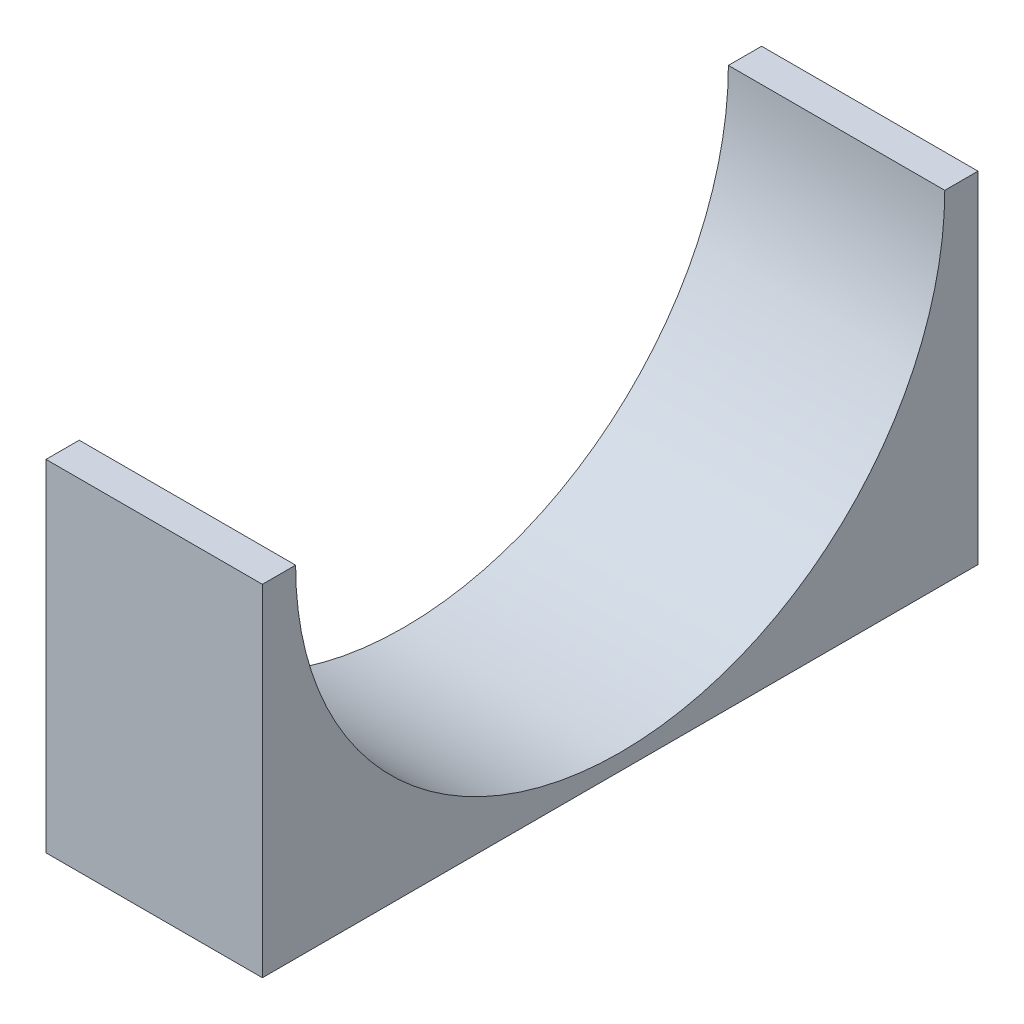
SolidWorks part; units mm, degrees
ref_plane "Front Plane" through (0, 0, 0) normal (0, 0, 1) x (1, 0, 0)
ref_plane "Top Plane" through (0, 0, 0) normal (0, 1, 0) x (1, 0, 0)
ref_plane "Right Plane" through (0, 0, 0) normal (1, 0, 0) x (0, 0, -1)
sketch "Sketch1" plane through (0, 0, 0) normal (0, 1, 0) x (1, 0, 0)
  line L1 (-12.7, 42) -> (12.7, 42)
  line L2 (-12.7, 42) -> (-12.7, -42)
  line L3 (-12.7, -42) -> (12.7, -42)
  line L4 (12.7, 42) -> (12.7, -42)
  line L5 (-12.7, 42) -> (12.7, -42) construction
  line L6 (-12.7, -42) -> (12.7, 42) construction
  point P0 (0, 0)
  dimension "D1" = 84
  dimension "D2" = 25.4
extrude "Boss-Extrude1" add sketch "Sketch1" along normal blind 40
sketch "Sketch4" plane through (0, 0, 0) normal (1, 0, 0) x (0, 0, -1)
  line L0 (-42, 40) -> (42, 40) construction
  circle A0 centre (0, 40) radius 38.1
  dimension "D1" = 76.2
extrude "Cut-Extrude1" cut sketch "Sketch4" along normal blind 15 and the other way blind 15
